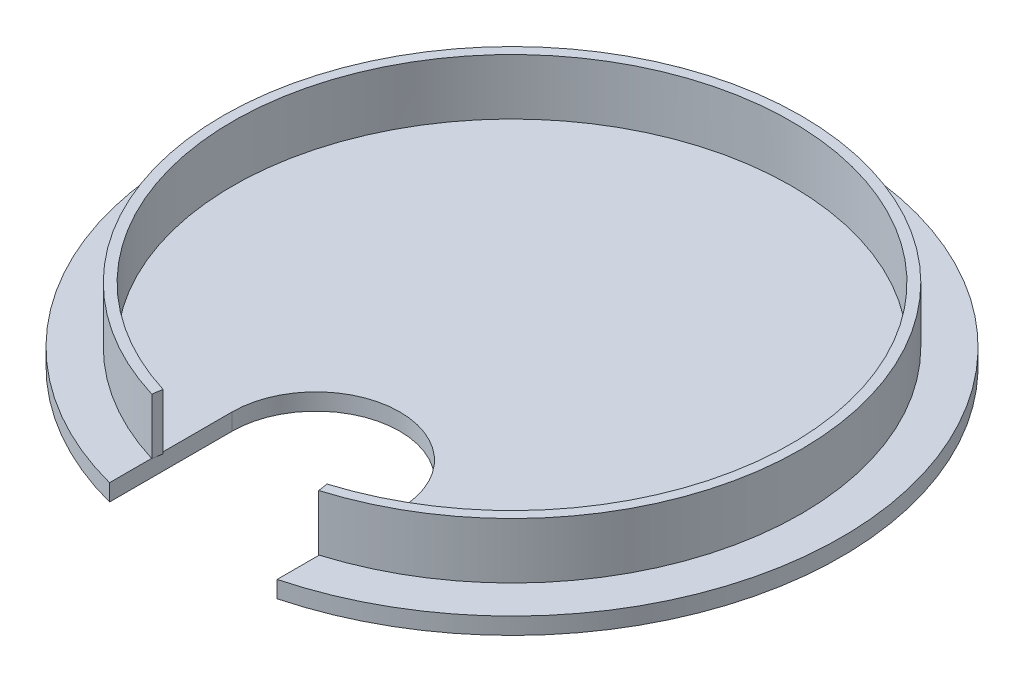
SolidWorks part; units mm, degrees
ref_plane "Front Plane" through (0, 0, 0) normal (0, 0, 1) x (1, 0, 0)
ref_plane "Top Plane" through (0, 0, 0) normal (0, 1, 0) x (1, 0, 0)
ref_plane "Right Plane" through (0, 0, 0) normal (1, 0, 0) x (0, 0, -1)
sketch "Sketch1" plane through (0, 0, 0) normal (0, 1, 0) x (1, 0, 0)
  circle A0 centre (0, 0) radius 59
extrude "Boss-Extrude1" add sketch "Sketch1" along normal blind 3
sketch "Sketch3" plane through (0, 3, 0) normal (0, 1, 0) x (1, 0, 0)
  circle A0 centre (0, 0) radius 51.75
extrude "Boss-Extrude2" add sketch "Sketch3" along normal blind 10
sketch "Sketch4" plane through (0, 13, 0) normal (0, 1, 0) x (1, 0, 0)
  circle A0 centre (0, 0) radius 50
extrude "Cut-Extrude2" cut sketch "Sketch4" against normal blind 10
scale "Scale1" scale about centroid uniform scaling yes scale factor 0.5
sketch "Sketch5" plane through (0, 2.7234, 0) normal (0, 1, 0) x (1, 0, 0)
  circle A0 centre (0, -17.5481) radius 7.5
extrude "Cut-Extrude3" cut sketch "Sketch5" against normal blind 15
sketch "Sketch6" plane through (0, 7.7234, 0) normal (0, 1, 0) x (1, 0, 0)
  circle A0 centre (0, -25.5138) radius 7.5
extrude "Cut-Extrude4" cut sketch "Sketch6" against normal blind 15
sketch "Sketch7" plane through (0, 7.7234, 0) normal (0, 1, 0) x (1, 0, 0)
  circle A0 centre (0, -20.6925) radius 7.5
extrude "Cut-Extrude5" cut sketch "Sketch7" against normal blind 15 contours A0
sketch "Sketch8" plane through (0, 2.7234, 0) normal (0, 1, 0) x (1, 0, 0)
  line L1 (-7.5, -17.5481) -> (7.5, -17.5481)
  line L2 (-7.5, -17.5481) -> (-7.5, -33.6348)
  line L3 (-7.5, -33.6348) -> (7.5, -33.6348)
  line L4 (7.5, -17.5481) -> (7.5, -33.6348)
  arc A0 (7.3334, -19.1203) -> (-7.3334, -19.1203) centre (0, -17.5481) ccw construction
extrude "Cut-Extrude6" cut sketch "Sketch8" against normal blind 15
